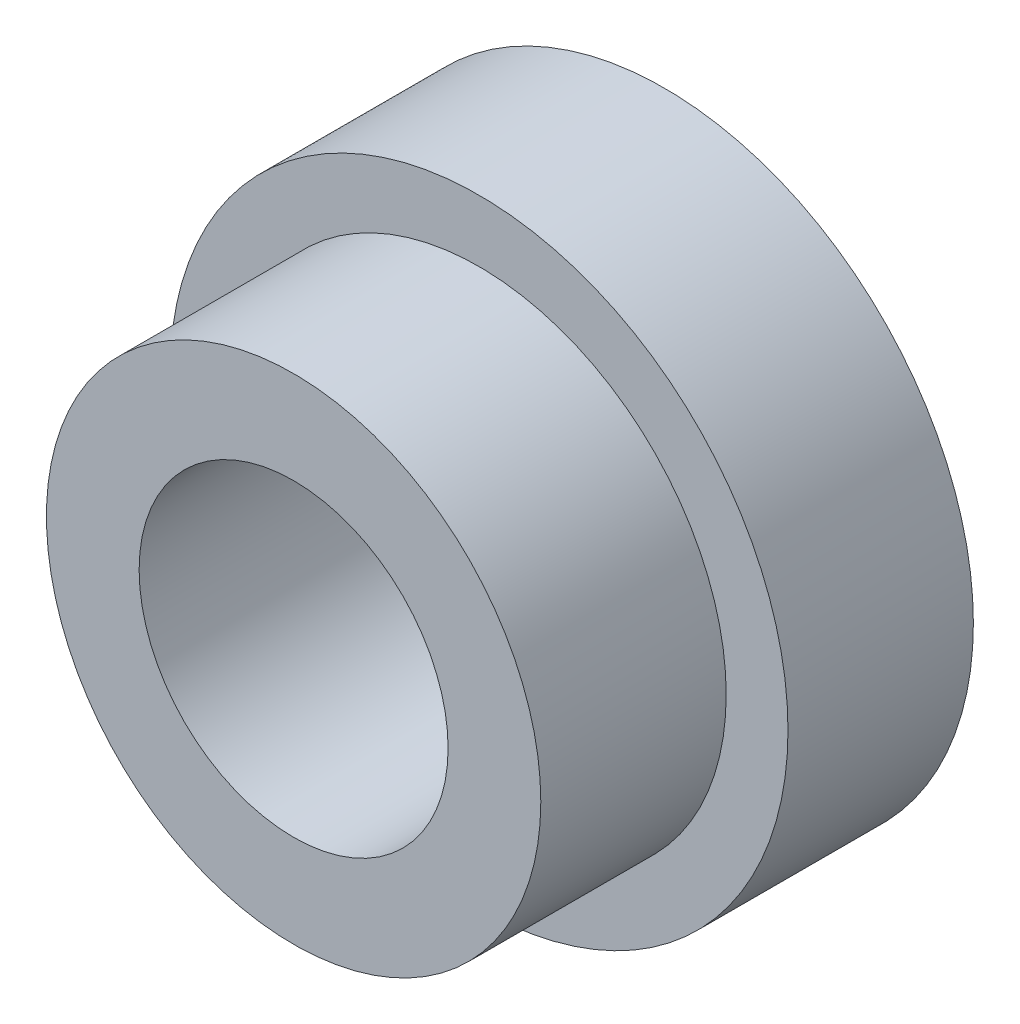
SolidWorks part; units mm, degrees
ref_plane "Front Plane" through (0, 0, 0) normal (0, 0, 1) x (1, 0, 0)
ref_plane "Top Plane" through (0, 0, 0) normal (0, 1, 0) x (1, 0, 0)
ref_plane "Right Plane" through (0, 0, 0) normal (1, 0, 0) x (0, 0, -1)
sketch "Sketch1" plane through (0, 0, 0) normal (0, 0, 1) x (1, 0, 0)
  circle A0 centre (0, 0) radius 5
  dimension "D1" = 10
extrude "Boss-Extrude1" add sketch "Sketch1" along normal blind 3
sketch "Sketch2" plane through (0, 0, 3) normal (0, 0, 1) x (1, 0, 0)
  circle A0 centre (0, 0) radius 4
  dimension "D1" = 8
extrude "Boss-Extrude2" add sketch "Sketch2" along normal blind 3
sketch "Sketch3" plane through (0, 0, 6) normal (0, 0, 1) x (1, 0, 0)
  circle A0 centre (0, 0) radius 2.5
  dimension "D1" = 5
extrude "Cut-Extrude1" cut sketch "Sketch3" against normal through all
